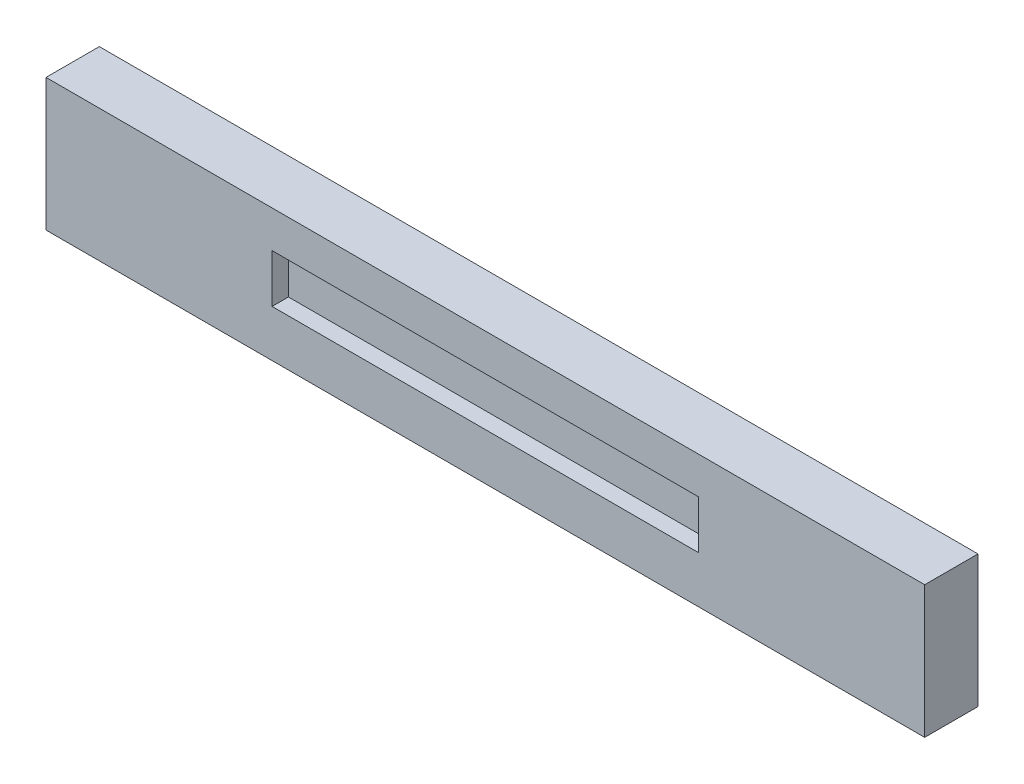
SolidWorks part; units mm, degrees
ref_plane "Front Plane" through (0, 0, 0) normal (0, 0, 1) x (1, 0, 0)
ref_plane "Top Plane" through (0, 0, 0) normal (0, 1, 0) x (1, 0, 0)
ref_plane "Right Plane" through (0, 0, 0) normal (1, 0, 0) x (0, 0, -1)
other "Configuration Table"
sketch "Sketch1" plane through (0, 0, 0) normal (0, 0, 1) x (1, 0, 0)
  line L1 (0, 0) -> (618, 0)
  line L2 (0, 0) -> (0, 93)
  line L3 (0, 93) -> (618, 93)
  line L4 (618, 0) -> (618, 93)
extrude "CEK_taze_on_pu_37.5_1" add sketch "Sketch1" along normal blind 37.5 from offset 1 separate body
sketch "Sketch2" plane through (0, 0, 0) normal (0, 0, 1) x (1, 0, 0)
  line L1 (159, 33) -> (459, 33)
  line L2 (159, 33) -> (159, 67)
  line L3 (159, 67) -> (459, 67)
  line L4 (459, 33) -> (459, 67)
extrude "CEK_taze_on_pu_37.5_2" cut sketch "Sketch2" along normal blind 14 from offset 27
